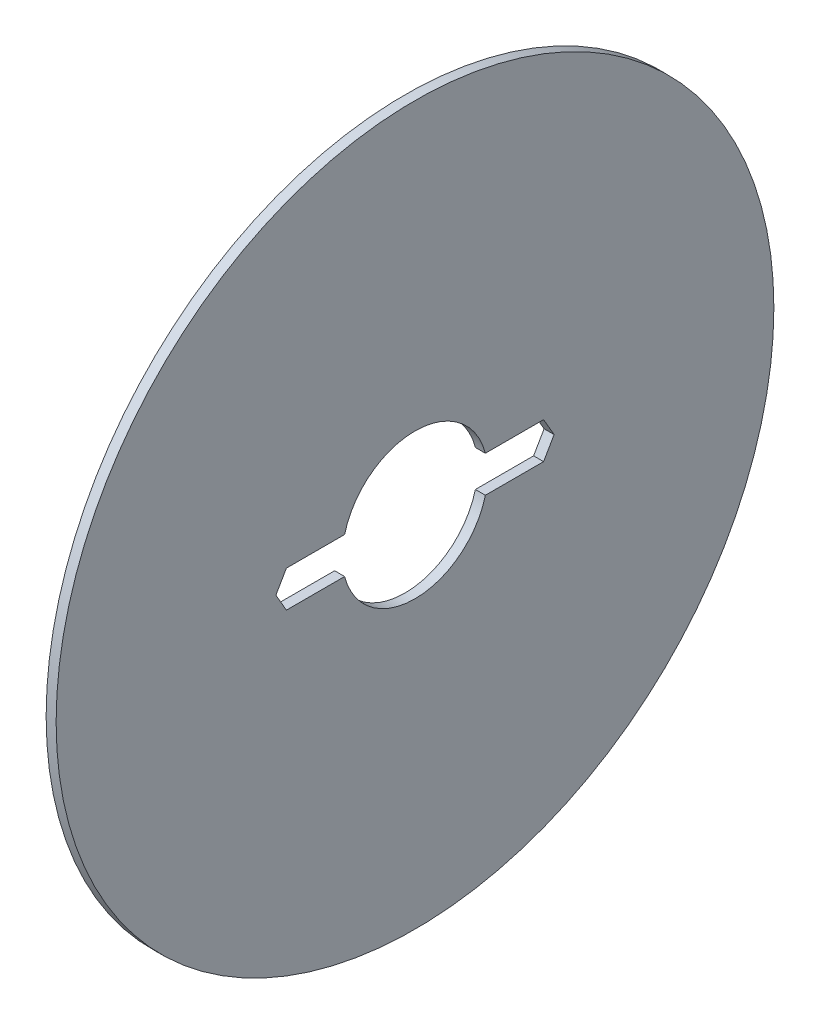
SolidWorks part; units mm, degrees
ref_plane "Front Plane" through (0, 0, 0) normal (0, 0, 1) x (1, 0, 0)
ref_plane "Top Plane" through (0, 0, 0) normal (0, 1, 0) x (1, 0, 0)
ref_plane "Right Plane" through (0, 0, 0) normal (1, 0, 0) x (0, 0, -1)
sketch "Sketch1" plane through (0, 0, 0) normal (1, 0, 0) x (0, 0, -1)
  line L0 (-19.75, 0) -> (19.75, 0) construction
  line L1 (5.9226, 1) -> (3.873, 1)
  line L2 (-3.873, 1) -> (-5.9226, 1)
  line L3 (5.9226, -1) -> (3.873, -1)
  line L4 (-3.873, -1) -> (-5.9226, -1)
  line L5 (5.9226, 1) -> (6.5, 1)
  line L6 (-7.6547, 0) -> (-7.0774, -1)
  line L7 (-7.0774, -1) -> (-5.9226, -1)
  line L8 (-5.9226, 1) -> (-7.0774, 1)
  line L9 (-7.0774, 1) -> (-7.6547, 0)
  line L10 (7.6547, 0) -> (7.0774, 1)
  line L11 (7.0774, 1) -> (6.5, 1)
  line L12 (6.5, -1) -> (7.0774, -1)
  line L13 (7.0774, -1) -> (7.6547, 0)
  line L14 (5.9226, -1) -> (6.5, -1)
  circle A0 centre (0, 0) radius 19.75
  arc A1 (-3.873, -1) -> (3.873, -1) centre (0, 0) ccw
  arc A2 (6.5, -1) -> (6.5, 1) centre (6.5, 0) ccw construction
  arc A3 (-6.5, 1) -> (-6.5, -1) centre (-6.5, 0) ccw construction
  arc A4 (3.873, 1) -> (-3.873, 1) centre (0, 0) ccw
  circle A5 centre (-6.5, 0) radius 1 construction
  circle A6 centre (6.5, 0) radius 1 construction
  point P9 (0, 0)
  dimension "D1" = 2
  dimension "D2" = 8
  dimension "D3" = 39.5
extrude "Boss-Extrude1" add sketch "Sketch1" along normal blind 0.55
